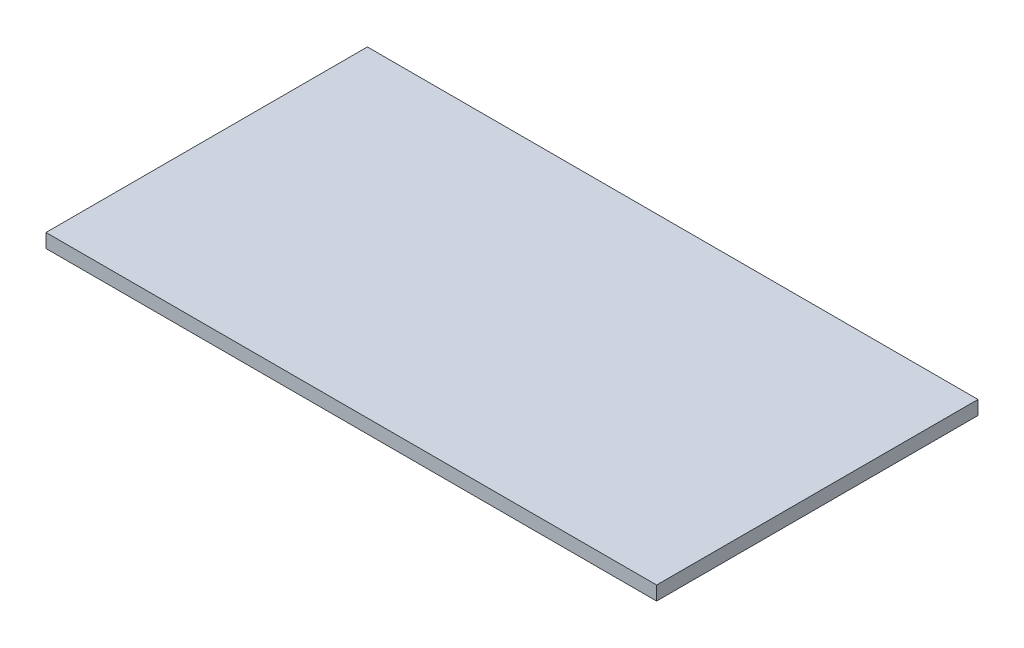
SolidWorks part; units mm, degrees
ref_plane "Front Plane" through (0, 0, 0) normal (0, 0, 1) x (1, 0, 0)
ref_plane "Top Plane" through (0, 0, 0) normal (0, 1, 0) x (1, 0, 0)
ref_plane "Right Plane" through (0, 0, 0) normal (1, 0, 0) x (0, 0, -1)
sketch "Sketch1" plane through (0, 0, 0) normal (0, 1, 0) x (1, 0, 0)
  line L1 (-57, 30) -> (57, 30)
  line L2 (-57, 30) -> (-57, -30)
  line L3 (-57, -30) -> (57, -30)
  line L4 (57, 30) -> (57, -30)
  line L5 (-57, 30) -> (57, -30) construction
  line L6 (-57, -30) -> (57, 30) construction
  point P0 (0, 0)
  dimension "D1" = 60
  dimension "D2" = 114
extrude "Boss-Extrude1" add sketch "Sketch1" along normal blind 2.6
